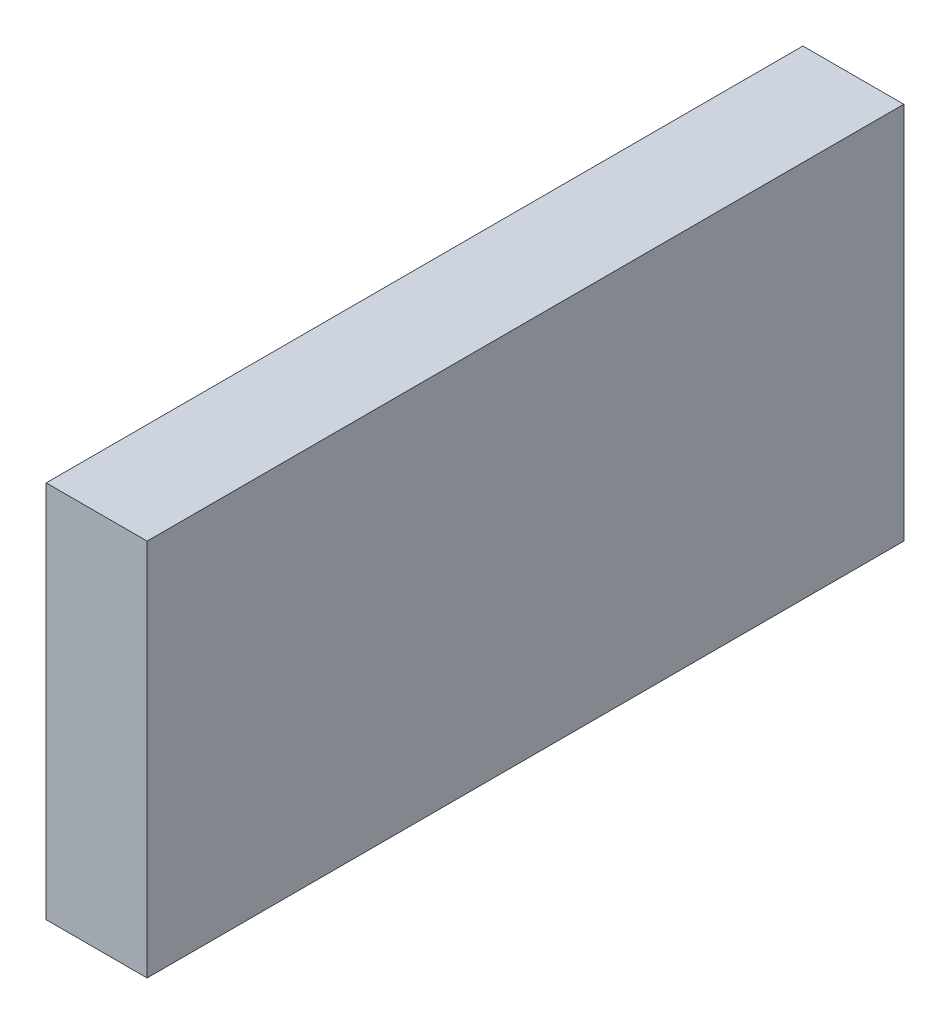
SolidWorks part; units mm, degrees
ref_plane "Front Plane" through (0, 0, 0) normal (0, 0, 1) x (1, 0, 0)
ref_plane "Top Plane" through (0, 0, 0) normal (0, 1, 0) x (1, 0, 0)
ref_plane "Right Plane" through (0, 0, 0) normal (1, 0, 0) x (0, 0, -1)
sketch "Sketch1" plane through (0, 0, 0) normal (0, 0, 1) x (1, 0, 0)
  line L1 (-2, 7.5) -> (2, 7.5)
  line L2 (-2, 7.5) -> (-2, -7.5)
  line L3 (-2, -7.5) -> (2, -7.5)
  line L4 (2, 7.5) -> (2, -7.5)
  line L5 (-2, 7.5) -> (2, -7.5) construction
  line L6 (-2, -7.5) -> (2, 7.5) construction
  point P0 (0, 0)
  dimension "D1" = 4
  dimension "D2" = 15
extrude "Boss-Extrude1" add sketch "Sketch1" along normal blind 30
